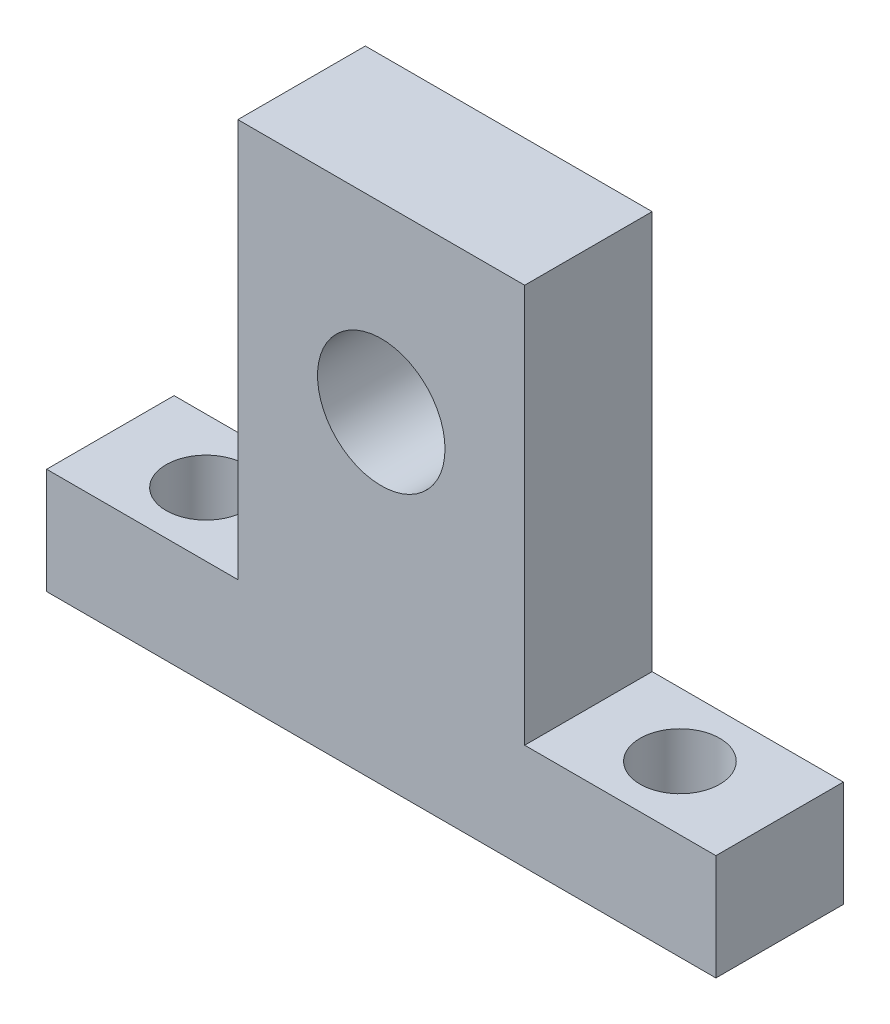
SolidWorks part; units mm, degrees
ref_plane "Front Plane" through (0, 0, 0) normal (0, 0, 1) x (1, 0, 0)
ref_plane "Top Plane" through (0, 0, 0) normal (0, 1, 0) x (1, 0, 0)
ref_plane "Right Plane" through (0, 0, 0) normal (1, 0, 0) x (0, 0, -1)
sketch "Sketch2" plane through (0, 0, 0) normal (0, 0, 1) x (1, 0, 0)
  line L0 (-32.2859, 18.5273) -> (-32.2859, 25.1773)
  line L1 (-32.2859, 25.1773) -> (-20.2859, 25.1773)
  line L2 (-20.2859, 25.1773) -> (-20.2859, 50.1773)
  line L3 (-20.2859, 50.1773) -> (-2.2859, 50.1773)
  line L4 (-2.2859, 50.1773) -> (-2.2859, 25.1773)
  line L5 (-2.2859, 25.1773) -> (9.7141, 25.1773)
  line L6 (9.7141, 25.1773) -> (9.7141, 18.5273)
  line L7 (9.7141, 18.5273) -> (-32.2859, 18.5273)
  line L8 (-11.2859, 50.1773) -> (-11.2859, 0) construction
  circle A1 centre (-11.2859, 38.7773) radius 4
  dimension "D5" = 8
  dimension "D1" = 6.65
  dimension "D2" = 42
  dimension "D3" = 18
  dimension "D4" = 12
  dimension "D6" = 20.25
  dimension "D7" = 25
  dimension "D8" = 6.65
extrude "Boss-Extrude1" add sketch "Sketch2" along normal blind 8
sketch "Sketch3" plane through (0, 25.1773, 0) normal (0, 1, 0) x (1, 0, 0)
  line L0 (-26.2859, 0) -> (-26.2859, -8) construction
  line L1 (-20.2859, 0) -> (-32.2859, 0) construction
  line L2 (-20.2859, -8) -> (-32.2859, -8) construction
  line L3 (3.7141, 0) -> (3.7141, -8) construction
  line L4 (9.7141, 0) -> (-2.2859, 0) construction
  line L5 (9.7141, -8) -> (-2.2859, -8) construction
  circle A0 centre (-26.2859, -4) radius 2.5
  circle A1 centre (3.4567, -4) radius 2.5
  dimension "D1" = 5
  dimension "D2" = 5
extrude "Cut-Extrude1" cut sketch "Sketch3" against normal up to surface (6.65 mm away) up to face at (-11.2859, 18.5273, 4)
